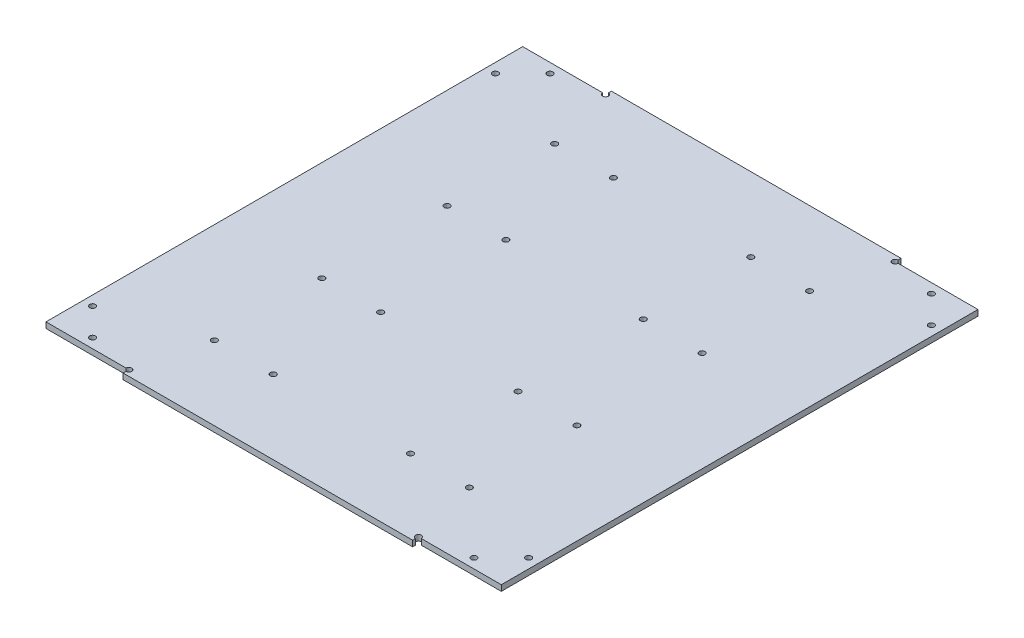
SolidWorks part; units mm, degrees
ref_plane "Plano frontal" through (0, 0, 0) normal (0, 0, 1) x (1, 0, 0)
ref_plane "Plano superior" through (0, 0, 0) normal (0, 1, 0) x (1, 0, 0)
ref_plane "Plano direito" through (0, 0, 0) normal (1, 0, 0) x (0, 0, -1)
sketch "Esboço1" plane through (0, 0, 0) normal (0, 0, 1) x (1, 0, 0)
  line L0 (-200, 0) -> (200, 0)
  line L1 (150, 26) -> (144.1525, 26)
  line L2 (0, 0) -> (0, 26) construction
  line L3 (150, 26) -> (-150, 26) construction
  line L4 (150, 20) -> (150, 26) construction
  line L5 (144.1525, 26) -> (138.2626, 30.3047)
  line L6 (150, 20) -> (-150, 20)
  line L7 (138.2626, 30.3047) -> (153.1541, 34.1943)
  line L8 (139.0472, 52.7422) -> (160.0854, 40.2451)
  line L9 (139.0472, 52.7422) -> (150.7846, 58.3876)
  line L10 (150.7846, 58.3876) -> (140, 61)
  line L11 (160.0854, 40.2451) -> (137.5975, 43.4375)
  line L12 (137.5975, 43.4375) -> (153.1541, 34.1943)
  line L13 (140, 61) -> (200, 61)
  line L14 (289.6201, 30.5) -> (200, 30.5) construction
  line L15 (200, 30.5) -> (200, 61) construction
  line L16 (250, 61) -> (262.9328, 109.2659) construction
  line L17 (210, -30) -> (290, -30)
  line L18 (260.0199, 109.9857) -> (240.6084, 37.5413)
  line L19 (246.404, 35.9884) -> (265.8154, 108.4328)
  line L20 (240.6084, 37.5413) -> (246.404, 35.9884) construction
  line L21 (243.5062, 36.7648) -> (250, 61) construction
  line L22 (-243.5062, 36.7648) -> (-250, 61) construction
  line L23 (-240.6084, 37.5413) -> (-246.404, 35.9884) construction
  line L24 (-250, 61) -> (-262.9328, 109.2659) construction
  line L25 (-200, 30.5) -> (-200, 61) construction
  line L26 (-289.6201, 30.5) -> (-200, 30.5) construction
  line L27 (-150, 20) -> (-150, 26) construction
  line L28 (-246.404, 35.9884) -> (-265.8154, 108.4328)
  line L29 (-260.0199, 109.9857) -> (-240.6084, 37.5413)
  line L30 (-210, -30) -> (-290, -30)
  line L31 (-140, 61) -> (-200, 61)
  line L32 (-137.5975, 43.4375) -> (-153.1541, 34.1943)
  line L33 (-160.0854, 40.2451) -> (-137.5975, 43.4375)
  line L34 (-150.7846, 58.3876) -> (-140, 61)
  line L35 (-139.0472, 52.7422) -> (-150.7846, 58.3876)
  line L36 (-139.0472, 52.7422) -> (-160.0854, 40.2451)
  line L37 (-138.2626, 30.3047) -> (-153.1541, 34.1943)
  line L38 (-144.1525, 26) -> (-138.2626, 30.3047)
  line L39 (-150, 26) -> (-144.1525, 26)
  arc A0 (150, 20) -> (150, 26) centre (150, 23) ccw
  arc A1 (200, 61) -> (260.0199, 109.9857) centre (250, 61) cw
  arc A2 (200, 0) -> (210, -30) centre (250, 0) ccw
  arc A3 (290, -30) -> (289.6201, 30.5) centre (250, 0) ccw
  arc A4 (240.6084, 37.5413) -> (246.404, 35.9884) centre (243.5062, 36.7648) ccw
  arc A5 (265.8154, 108.4328) -> (289.6201, 30.5) centre (250, 61) cw
  arc A6 (-265.8154, 108.4328) -> (-289.6201, 30.5) centre (-250, 61) ccw
  arc A7 (-240.6084, 37.5413) -> (-246.404, 35.9884) centre (-243.5062, 36.7648) cw
  arc A8 (-290, -30) -> (-289.6201, 30.5) centre (-250, 0) cw
  arc A9 (-200, 0) -> (-210, -30) centre (-250, 0) cw
  arc A10 (-200, 61) -> (-260.0199, 109.9857) centre (-250, 61) ccw
  arc A11 (-150, 20) -> (-150, 26) centre (-150, 23) cw
  point P45 (0, 20)
  point P54 (0, 20)
  dimension "D7" = 30
  dimension "D9" = 15
  dimension "D10" = 6
  dimension "D11" = 75
  dimension "D1" = 3
  dimension "D6" = 50
  dimension "D2" = 200
  dimension "D3" = 20
  dimension "D4" = 150
  dimension "D5" = 61
  dimension "D8" = 140
extrude "Ressalto-extrusão2" add sketch "Esboço1" along normal blind 6
sketch "Esboço4" plane through (215.1054, -57.6373, 0) normal (0.9659, -0.2588, 0) x (0, 0, -1)
  line L0 (-6, 173.5362) -> (0, 173.5362) construction
  line L1 (-3, 123.5362) -> (-3, 173.5362) construction
  line L2 (247, 62.5362) -> (247, 123.5362)
  line L9 (247, 123.5362) -> (47, 123.5362)
  line L27 (-41.2176, 30.2962) -> (35.2176, 30.2962)
  line L28 (47, 62.5362) -> (247, 62.5362)
  line L29 (247, 62.5362) -> (247, 123.5362) construction
  arc A1 (47, 123.5362) -> (-3, 173.5362) centre (-3, 123.5362) ccw
  arc A3 (-3, 173.5362) -> (-42.6201, 93.0362) centre (-3, 123.5362) ccw
  arc A4 (-42.6201, 93.0362) -> (-41.2176, 30.2962) centre (-3, 62.5362) ccw
  arc A5 (35.2176, 30.2962) -> (47, 62.5362) centre (-3, 62.5362) ccw
  dimension "D4" = 50
  dimension "D9" = 50
  dimension "D10" = 50
  dimension "D1" = 61
  dimension "D2" = 123.5362
  dimension "D3" = 200
  dimension "D5" = 30.5
  dimension "D6" = 61
  dimension "D7" = 32.24
extrude "Ressalto-extrusão3" add sketch "Esboço4" along normal blind 6 separate body
sketch "Esboço5" plane through (0, 0, 6) normal (0, 0, 1) x (1, 0, 0)
  line L0 (-341.8058, 0) -> (-379.5634, 0)
  line L1 (0, 0) -> (-124.2027, 0)
  line L2 (0, 0) -> (0, 200.2314)
  line L3 (0, 200.2314) -> (-379.5634, 200.2314)
  line L4 (-379.5634, 0) -> (-379.5634, 200.2314)
  line L6 (-341.8058, 0) -> (-341.8058, -126.6701)
  line L7 (-341.8058, -126.6701) -> (-124.2027, -126.6701)
  line L8 (-124.2027, 0) -> (-124.2027, -126.6701)
extrude "Corte-extrusão2" cut sketch "Esboço5" against normal blind 10
sketch "Esboço7" plane through (0, 0, 6) normal (0, 0, 1) x (1, 0, 0)
  line L0 (239.1849, 32.2287) -> (222.9466, -28.3735) construction
  line L1 (0, 26) -> (235.9083, 26)
  line L2 (0, 26) -> (0, 20)
  line L3 (0, 20) -> (235.9083, 20)
  line L4 (235.9083, 26) -> (235.9083, 20)
  line L5 (150, 20) -> (0, 20) construction
  line L6 (0, 0) -> (0, 20) construction
  dimension "D1" = 6
extrude "Ressalto-extrusão4" add sketch "Esboço7" against normal up to vertex (253 mm away) separate body
combine bodies "Combinar1" operation type subtract main body 112 bodies to subtract 111 106
sketch "Esboço8" plane through (0, 0, 6) normal (0, 0, 1) x (1, 0, 0)
  line L0 (235.9083, 20) -> (150, 20) construction
  line L1 (150, 26) -> (156.266, 26)
  line L2 (150, 26) -> (150, 20)
  line L3 (150, 20) -> (156.266, 20)
  line L4 (156.266, 26) -> (156.266, 20)
extrude "Corte-extrusão3" cut sketch "Esboço8" against normal up to vertex (6 mm away)
sketch "Esboço9" plane through (0, 26, 0) normal (0, 1, 0) x (1, 0, 0)
  line L0 (197.624, 10) -> (225.9083, 38.2843) construction
  line L1 (235.9083, 247) -> (235.9083, 0) construction
  line L2 (150, 0) -> (235.9083, 0) construction
  line L3 (71.1619, 182.1009) -> (132.1224, 182.1009) construction
  line L4 (132.1224, 182.1009) -> (132.1224, 70.6905) construction
  line L5 (132.1224, 70.6905) -> (71.1619, 70.6905) construction
  line L6 (71.1619, 70.6905) -> (71.1619, 182.1009) construction
  circle A0 centre (225.9083, 38.2843) radius 3
  circle A1 centre (197.624, 10) radius 3
  circle A2 centre (71.1619, 70.6905) radius 3
  circle A3 centre (132.1224, 70.6905) radius 3
  circle A4 centre (71.1619, 182.1009) radius 3
  circle A5 centre (132.1224, 182.1009) radius 3
  dimension "D1" = 6
  dimension "D2" = 6
  dimension "D7" = 6
  dimension "D3" = 45
  dimension "D4" = 10
  dimension "D5" = 10
  dimension "D6" = 40
extrude "Corte-extrusão4" cut sketch "Esboço9" against normal through all
mirror "Espelhar1" about plane through (0, 26, -247) normal (-1, 0, 0) of bodies 115
mirror "Espelhar3" about plane through (0, 0, -247) normal (0, 0, 1) of bodies 116
sketch "Esboço10" plane through (0, 20, 0) normal (0, -1, 0) x (-1, 0, 0)
  circle A0 centre (150, 0) radius 3
  circle A1 centre (-150, 0) radius 3
  circle A2 centre (-150, 494) radius 3
  circle A3 centre (150, 494) radius 3
  dimension "D1" = 6
extrude "Corte-extrusão5" cut sketch "Esboço10" against normal through all
